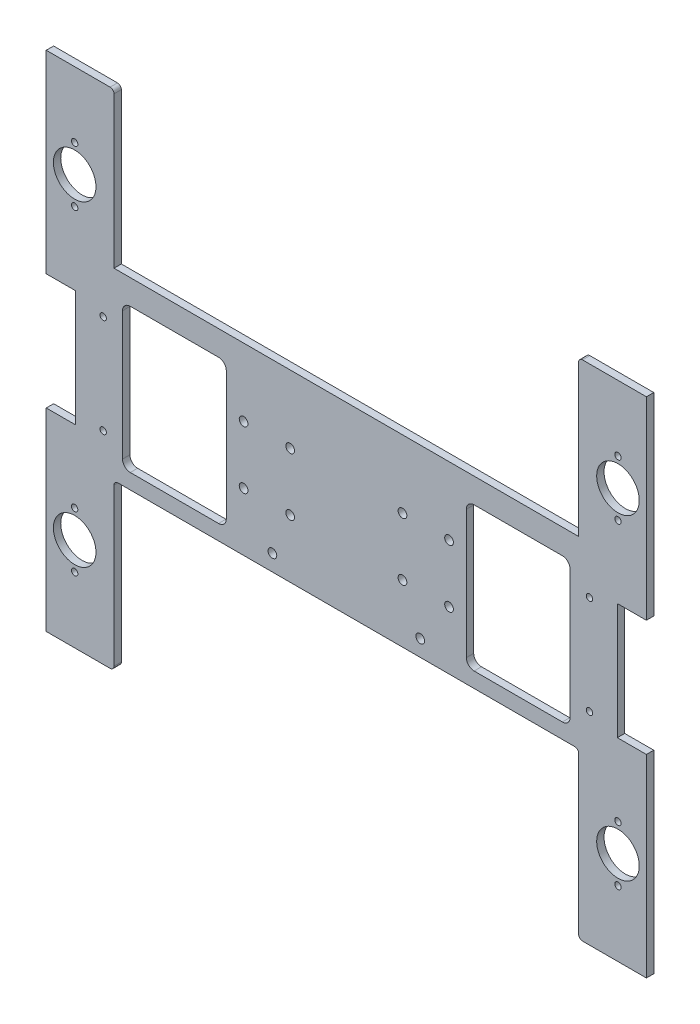
SolidWorks part; units mm, degrees
ref_plane "Front Plane" through (0, 0, 0) normal (0, 0, 1) x (1, 0, 0)
ref_plane "Top Plane" through (0, 0, 0) normal (0, 1, 0) x (1, 0, 0)
ref_plane "Right Plane" through (0, 0, 0) normal (1, 0, 0) x (0, 0, -1)
ref_plane "Plane1" through (0, 150, 0) normal (0, 1, 0) x (1, 0, 0)
ref_plane "Plane2" through (0, -150, 0) normal (0, 1, 0) x (1, 0, 0)
ref_plane "Plane3" through (150, 0, 0) normal (1, 0, 0) x (0, 0, -1)
ref_plane "Plane4" through (-150, 0, 0) normal (1, 0, 0) x (0, 0, -1)
sketch "Sketch2" plane through (0, 0, 0) normal (0, 0, 1) x (1, 0, 0)
  line L0 (0, -10.2) -> (0, 50.0764) construction
  line L5 (-53.06, 39.945) -> (-53.06, 10.055) construction
  line L23 (-155, 155) -> (-122, 155)
  line L24 (139.6652, 116) -> (168.3348, 116) construction
  line L31 (-155, -105) -> (-122, -105)
  line L40 (-152.1866, -81.0661) -> (-123.5266, -81.0661) construction
  line L42 (-120, 153) -> (-120, 75)
  line L43 (-120, 75) -> (120, 75)
  line L47 (-66, 62.1714) -> (-111.5977, 62.1714)
  line L48 (66, 62.1714) -> (111.5977, 62.1714)
  line L49 (62, 58.1714) -> (62, -8.1714)
  line L50 (66, -12.1714) -> (111.5977, -12.1714)
  line L51 (115.5977, 58.1714) -> (115.5977, -8.1714)
  line L52 (62, 62.1714) -> (115.5977, -12.1714) construction
  line L53 (62, -12.1714) -> (115.5977, 62.1714) construction
  line L54 (-62, 58.1714) -> (-62, -8.1714)
  line L55 (-66, -12.1714) -> (-111.5977, -12.1714)
  line L56 (-115.5977, 58.1714) -> (-115.5977, -8.1714)
  line L57 (177.1787, -66.0847) -> (177.1787, 11.9153) construction
  line L70 (-125.5977, 50.5) -> (-125.5977, -0.5) construction
  line L73 (-155, 155) -> (-155, 55)
  line L74 (162.5, 25) -> (139.6652, 25) construction
  line L75 (-120, -103) -> (-120, -22)
  line L76 (-118, -20) -> (118, -20)
  line L79 (-155, -5) -> (-155, -105)
  line L80 (-155, -5) -> (-140, -5)
  line L82 (-155, 55) -> (-140, 55)
  line L83 (-140, -5) -> (-140, 55)
  line L84 (-145.4163, 25) -> (-140, 55) construction
  line L85 (-145.4163, 25) -> (-140, -5) construction
  line L88 (145.4163, 25) -> (140, -5) construction
  line L89 (145.4163, 25) -> (140, 55) construction
  line L90 (125.5977, 50.5) -> (125.5977, -0.5) construction
  line L91 (140, -5) -> (140, 55)
  line L92 (155, 55) -> (140, 55)
  line L93 (155, -5) -> (140, -5)
  line L94 (155, -5) -> (155, -105)
  line L95 (155, 155) -> (155, 55)
  line L96 (120, -103) -> (120, -22)
  line L97 (155, -105) -> (122, -105)
  line L98 (155, 155) -> (122, 155)
  line L99 (120, 153) -> (120, 75)
  circle A1 centre (-140.3098, 121.0768) radius 1.65
  circle A2 centre (-140.3098, 92.4072) radius 1.65
  circle A3 centre (140.3098, 121.0768) radius 1.65
  circle A4 centre (140.3098, 92.4072) radius 1.65
  circle A9 centre (140.3098, 106.742) radius 11
  circle A10 centre (-140.3098, 106.742) radius 11
  circle A17 centre (125.5977, -0.5) radius 1.65
  circle A18 centre (125.5977, 50.5) radius 1.65
  circle A19 centre (-125.5977, -0.5) radius 1.65
  circle A20 centre (-125.5977, 50.5) radius 1.65
  circle A27 centre (-29, 10.055) radius 2.25
  circle A32 centre (-29, 39.945) radius 2.25
  circle A33 centre (-53.06, 39.945) radius 2.25
  circle A34 centre (-53.06, 10.055) radius 2.25
  circle A35 centre (53.06, 10.055) radius 2.25
  circle A36 centre (29, 10.055) radius 2.25
  circle A37 centre (29, 39.945) radius 2.25
  circle A38 centre (53.06, 39.945) radius 2.25
  arc A47 (-120, 153) -> (-122, 155) centre (-122, 153) ccw
  arc A48 (62, -8.1714) -> (66, -12.1714) centre (66, -8.1714) ccw
  arc A49 (111.5977, -12.1714) -> (115.5977, -8.1714) centre (111.5977, -8.1714) ccw
  arc A50 (111.5977, 62.1714) -> (115.5977, 58.1714) centre (111.5977, 58.1714) cw
  arc A51 (66, 62.1714) -> (62, 58.1714) centre (66, 58.1714) ccw
  arc A52 (-111.5977, 62.1714) -> (-115.5977, 58.1714) centre (-111.5977, 58.1714) ccw
  arc A53 (-66, 62.1714) -> (-62, 58.1714) centre (-66, 58.1714) cw
  arc A54 (-62, -8.1714) -> (-66, -12.1714) centre (-66, -8.1714) cw
  arc A55 (-111.5977, -12.1714) -> (-115.5977, -8.1714) centre (-111.5977, -8.1714) cw
  circle A68 centre (140.3098, -71.0768) radius 1.65
  circle A69 centre (140.3098, -42.4072) radius 1.65
  circle A70 centre (140.3098, -56.742) radius 11
  circle A71 centre (-140.3098, -56.742) radius 11
  circle A72 centre (-140.3098, -42.4072) radius 1.65
  circle A73 centre (-140.3098, -71.0768) radius 1.65
  arc A76 (-120, -22) -> (-118, -20) centre (-118, -22) cw
  arc A77 (-120, -103) -> (-122, -105) centre (-122, -103) cw
  arc A79 (120, -22) -> (118, -20) centre (118, -22) ccw
  arc A80 (120, -103) -> (122, -105) centre (122, -103) ccw
  arc A81 (120, 153) -> (122, 155) centre (122, 153) cw
  circle A82 centre (38.1799, -11.5638) radius 2.25
  circle A83 centre (-38.1799, -11.5638) radius 2.25
  point P0 (0, 0)
  point P2 (0, 0)
  point P4 (0, 150)
  point P7 (-145.4163, 25)
  point P11 (-125.5977, 25)
  point P12 (88.7989, 25)
  point P23 (-53.06, 25)
  point P24 (0, -20)
  point P33 (-140, 25)
  point P82 (177.1787, -27.0847)
  point P111 (-115.5977, 25)
  point P112 (145.4163, 25)
  point P122 (0, 75)
  point P132 (-62, 25)
  dimension "D3" = 51
  dimension "D7" = 155
  dimension "D8" = 3.3
  dimension "D9" = 120
  dimension "D10" = 22
  dimension "D11" = 74.3428
  dimension "D12" = 80
  dimension "D13" = 53.5977
  dimension "D16" = 62
  dimension "D17" = 15
  dimension "D18" = 60
  dimension "D19" = 3.3
  dimension "D6" = 14.3348
  dimension "D20" = 14.3348
  dimension "D21" = 130
  dimension "D23" = 4.5
  dimension "D24" = 45
  dimension "D25" = 4.5
  dimension "D26" = 4.5
  dimension "D27" = 29.89
  dimension "D29" = 24.06
  dimension "D31" = 4
  dimension "D32" = 130
  dimension "D4" = 3.3
  dimension "D5" = 10
  dimension "D22" = 29.89
  dimension "D28" = 24.06
  dimension "D30" = 29
  dimension "D14" = 2
extrude "Boss-Extrude1" add sketch "Sketch2" along normal blind 3.8
